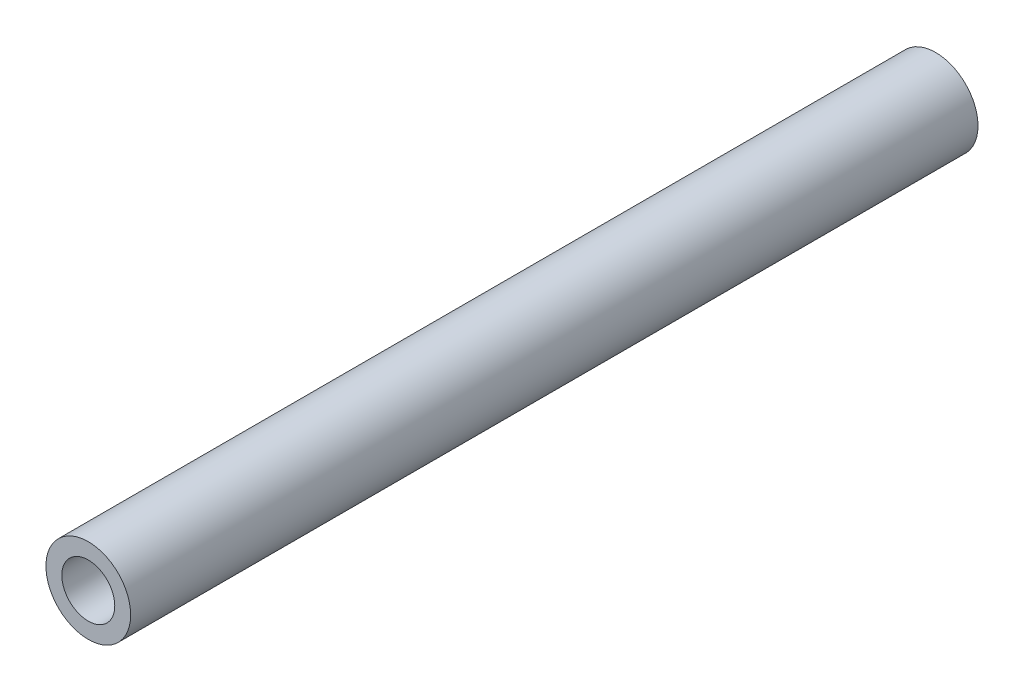
SolidWorks part; units mm, degrees
material "6063-O，挤压棒材(SS)"
ref_plane "前视基准面" through (0, 0, 0) normal (0, 0, 1) x (1, 0, 0)
ref_plane "上视基准面" through (0, 0, 0) normal (0, 1, 0) x (1, 0, 0)
ref_plane "右视基准面" through (0, 0, 0) normal (1, 0, 0) x (0, 0, -1)
sketch "草图1" plane through (0, 0, 0) normal (0, 0, 1) x (1, 0, 0)
  circle A0 centre (0, 0) radius 4
  circle A1 centre (0, 0) radius 2.5
  dimension "D1" = 8
  dimension "D2" = 5
extrude "凸台-拉伸1" add sketch "草图1" along normal blind 80
